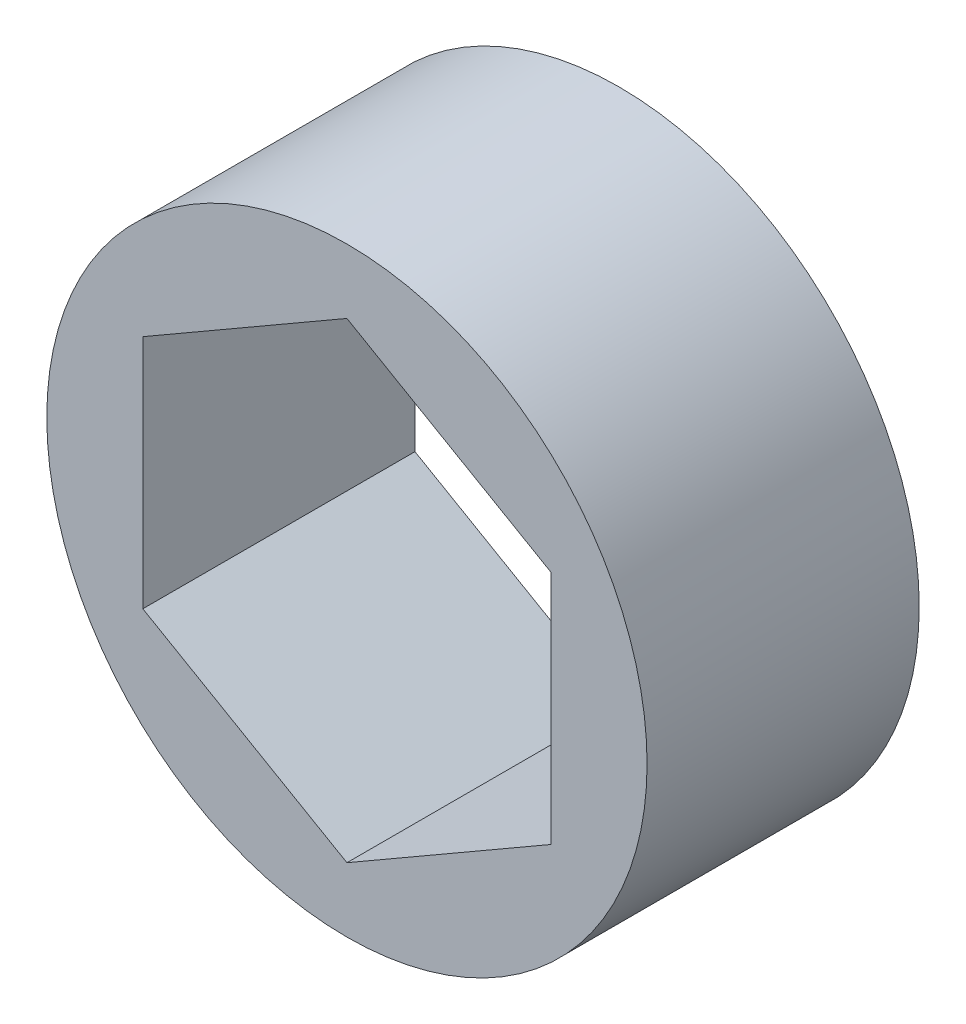
SolidWorks part; units mm, degrees
material "PET"
ref_plane "Front Plane" through (0, 0, 0) normal (0, 0, 1) x (1, 0, 0)
ref_plane "Top Plane" through (0, 0, 0) normal (0, 1, 0) x (1, 0, 0)
ref_plane "Right Plane" through (0, 0, 0) normal (1, 0, 0) x (0, 0, -1)
sketch "Sketch1" plane through (0, 0, 0) normal (0, 0, 1) x (1, 0, 0)
  line L1 (0, 7.479) -> (-6.477, 3.7395)
  line L2 (-6.477, 3.7395) -> (-6.477, -3.7395)
  line L3 (-6.477, -3.7395) -> (0, -7.479)
  line L4 (0, -7.479) -> (6.477, -3.7395)
  line L5 (6.477, -3.7395) -> (6.477, 3.7395)
  line L6 (6.477, 3.7395) -> (0, 7.479)
  circle A0 centre (0, 0) radius 6.477 construction
  circle A1 centre (0, 0) radius 9.525
  dimension "D1" = 12.954
  dimension "D2" = 19.05
extrude "Boss-Extrude1" add sketch "Sketch1" along normal mid plane 8.636
